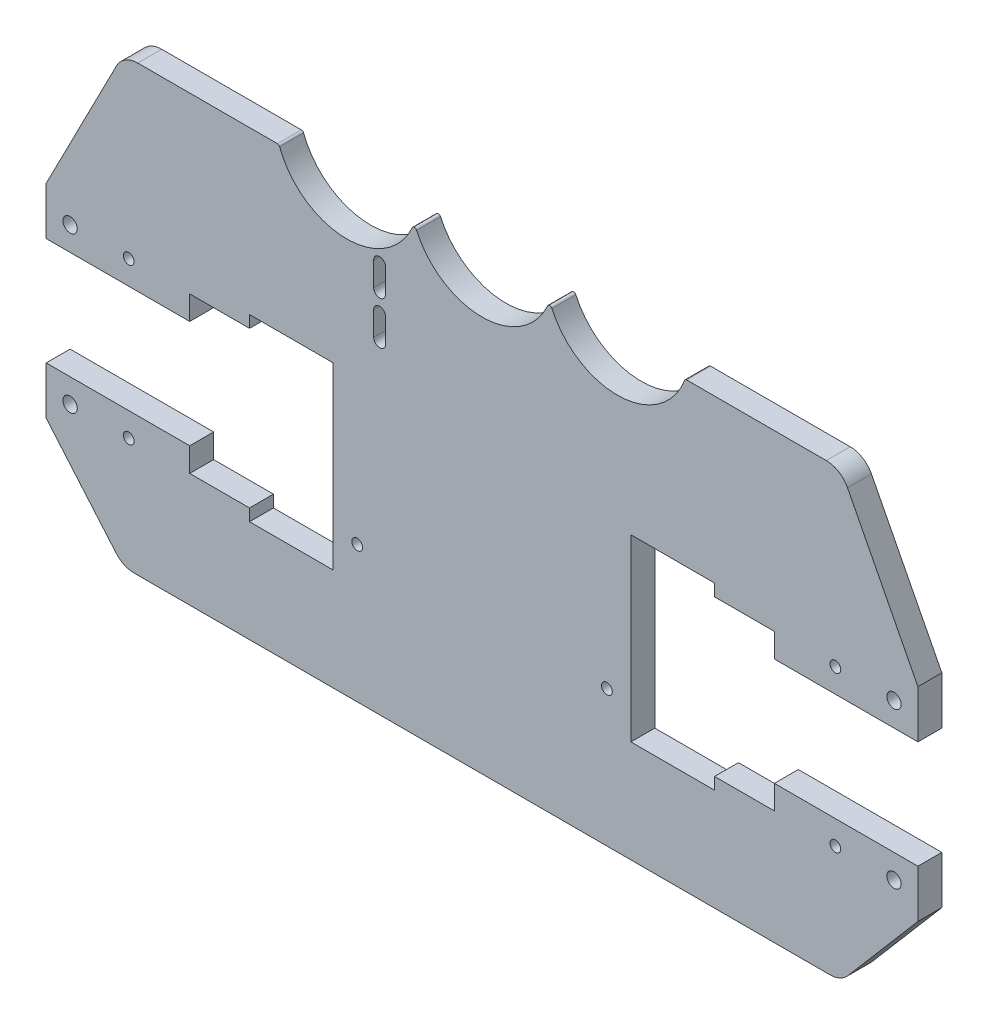
SolidWorks part; units mm, degrees
ref_plane "Plan de face" through (0, 0, 0) normal (0, 0, 1) x (1, 0, 0)
ref_plane "Plan de dessus" through (0, 0, 0) normal (0, 1, 0) x (1, 0, 0)
ref_plane "Plan de droite" through (0, 0, 0) normal (1, 0, 0) x (0, 0, -1)
sketch "Esquisse3" plane through (0, 0, 0) normal (0, 0, 1) x (1, 0, 0)
  line L0 (-182.2, 42.5) -> (-150, 105.2)
  line L1 (-182.2, 42.5) -> (182.2, 42.5)
  line L2 (-182.2, 42.5) -> (-182.2, -42.5)
  line L3 (-182.2, -42.5) -> (182.2, -42.5)
  line L4 (182.2, 42.5) -> (182.2, -42.5)
  line L5 (-150, 105.2) -> (150, 105.2)
  line L6 (-150, 105.2) -> (-150, 42.5)
  line L7 (-150, 42.5) -> (150, 42.5)
  line L8 (150, 105.2) -> (150, 42.5)
  line L9 (-150, -80.2) -> (150, -80.2)
  line L10 (-150, -80.2) -> (-150, -42.5)
  line L11 (-150, -42.5) -> (150, -42.5)
  line L12 (150, -80.2) -> (150, -42.5)
  line L13 (150, 105.2) -> (182.2, 42.5)
  line L14 (182.2, -42.5) -> (150, -80.2)
  line L15 (-150, -80.2) -> (-182.2, -42.5)
  dimension "D1" = 85
  dimension "D2" = 300
  dimension "D3" = 300
  dimension "D4" = 32.2
  dimension "D5" = 0
  dimension "D6" = 32.2
  dimension "D7" = 37.7
  dimension "D8" = 62.7
  dimension "D9" = 150
  dimension "D10" = 42.5
extrude "Boss.-Extru.1" add sketch "Esquisse3" along normal blind 10 contours L4 L1 L2 L3 | L8 L5 L6 L1 | L9 L12 L3 L10 | L6 L0 L1 | L15 L10 L3 | L14 L3 L12 | L13 L8 L1
sketch "Esquisse4" plane through (0, 0, 10) normal (0, 0, 1) x (1, 0, 0)
  line L1 (-182.2, 32.5) -> (-97.2, 32.5)
  line L2 (-182.2, 32.5) -> (-182.2, -32.5)
  line L3 (-182.2, -32.5) -> (-97.2, -32.5)
  line L4 (-97.2, 32.5) -> (-97.2, -32.5)
  line L5 (-97.2, -37.5) -> (-62.2, -37.5)
  line L6 (-97.2, -37.5) -> (-97.2, 37.5)
  line L7 (-97.2, 37.5) -> (-62.2, 37.5)
  line L8 (-62.2, -37.5) -> (-62.2, 37.5)
  line L9 (182.2, 32.5) -> (97.2, 32.5)
  line L10 (182.2, 32.5) -> (182.2, -32.5)
  line L11 (182.2, -32.5) -> (97.2, -32.5)
  line L12 (97.2, 32.5) -> (97.2, -32.5)
  line L13 (97.2, 37.5) -> (62.2, 37.5)
  line L14 (97.2, 37.5) -> (97.2, -37.5)
  line L15 (97.2, -37.5) -> (62.2, -37.5)
  line L16 (62.2, 37.5) -> (62.2, -37.5)
  line L17 (-182.2, 32.5) -> (-122.2, 32.5)
  line L18 (-182.2, 32.5) -> (-182.2, 22.5)
  line L19 (-182.2, 22.5) -> (-122.2, 22.5)
  line L20 (-122.2, 32.5) -> (-122.2, 22.5)
  line L21 (-182.2, -32.5) -> (-122.2, -32.5)
  line L22 (-182.2, -32.5) -> (-182.2, -22.5)
  line L23 (-182.2, -22.5) -> (-122.2, -22.5)
  line L24 (-122.2, -32.5) -> (-122.2, -22.5)
  line L25 (182.2, 32.5) -> (122.2, 32.5)
  line L26 (182.2, 32.5) -> (182.2, 22.5)
  line L27 (182.2, 22.5) -> (122.2, 22.5)
  line L28 (122.2, 32.5) -> (122.2, 22.5)
  line L29 (182.2, -32.5) -> (122.2, -32.5)
  line L30 (182.2, -32.5) -> (182.2, -22.5)
  line L31 (182.2, -22.5) -> (122.2, -22.5)
  line L32 (122.2, -32.5) -> (122.2, -22.5)
  line L34 (-182.2, 42.5) -> (-182.2, -42.5) construction
  line M16 (182.2, -42.5) -> (182.2, 42.5)
  line M20 (-182.2, 42.5) -> (-182.2, -42.5)
  dimension "D1" = 85
  dimension "D2" = 5
  dimension "D3" = 5
  dimension "D4" = 35
  dimension "D5" = 85
  dimension "D6" = 85
  dimension "D7" = 35
  dimension "D8" = 85
  dimension "D9" = 5
  dimension "D10" = 5
  dimension "D11" = 0
  dimension "D12" = 60
  dimension "D13" = 10
  dimension "D14" = 10
  dimension "D15" = 0
  dimension "D16" = 10
  dimension "D17" = 10
  dimension "D18" = 60
  dimension "D19" = 10
  dimension "D20" = 10
  dimension "D21" = 0
  dimension "D22" = 10
  dimension "D23" = 10
extrude "Enlèv. mat.-Extru.1" cut sketch "Esquisse4" against normal blind 10 contours L4 L1 L3 M20 | L5 L8 L7 L6 L4 | L13 L16 L15 L14 L12 | L9 L12 L11 M16
sketch "Esquisse5" plane through (0, 0, 10) normal (0, 0, 1) x (1, 0, 0)
  line L1 (-150, 105.2) -> (150, 105.2) construction
  arc A0 (28.2843, 105.2) -> (-28.2843, 105.2) centre (0, 115.2) cw
  arc A1 (-28.2843, 105.2) -> (-84.8528, 105.2) centre (-56.5685, 115.2) cw
  arc A2 (28.2843, 105.2) -> (84.8528, 105.2) centre (56.5685, 115.2) ccw
  point P4 (0, 80.2)
  point P6 (0, 80.2)
  point P11 (0, 80.2)
  point P12 (0, 80.2)
  point P13 (0, 0)
  point P14 (0, 0)
  point P15 (0, 80.2)
  dimension "D1" = 10
  dimension "D2" = 30
  dimension "D3" = 30
  dimension "D6" = 30
  dimension "D4" = 10
  dimension "D5" = 10
extrude "Enlèv. mat.-Extru.2" cut sketch "Esquisse5" against normal blind 10 and the other way through all
sketch "Esquisse11" plane through (0, 0, 10) normal (0, 0, 1) x (1, 0, 0)
  line L0 (182.2, 42.5) -> (182.2, 22.5) construction
  line L1 (-182.2, 42.5) -> (-162.2, 42.5)
  line L2 (-182.2, 42.5) -> (-182.2, 22.5)
  line L3 (-182.2, 22.5) -> (-162.2, 22.5)
  line L4 (-162.2, 42.5) -> (-162.2, 22.5)
  line L6 (182.2, -22.5) -> (182.2, -42.5) construction
  line L7 (-182.2, -22.5) -> (-162.2, -22.5)
  line L8 (-182.2, -22.5) -> (-182.2, -42.5)
  line L9 (-182.2, -42.5) -> (-162.2, -42.5)
  line L10 (-162.2, -22.5) -> (-162.2, -42.5)
  line L11 (182.2, 22.5) -> (122.2, 22.5) construction
  line L12 (162.2, 42.5) -> (182.2, 42.5)
  line L13 (162.2, 42.5) -> (162.2, 22.5)
  line L14 (162.2, 22.5) -> (182.2, 22.5)
  line L15 (182.2, 42.5) -> (182.2, 22.5)
  line L16 (162.2, -22.5) -> (182.2, -22.5)
  line L17 (162.2, -22.5) -> (162.2, -42.5)
  line L18 (162.2, -42.5) -> (182.2, -42.5)
  line L19 (182.2, -22.5) -> (182.2, -42.5)
  line L20 (-182.2, -22.5) -> (-182.2, -42.5) construction
  line L22 (-182.2, 42.5) -> (-182.2, 22.5) construction
  line L23 (182.2, -22.5) -> (122.2, -22.5) construction
  line L24 (-182.2, -22.5) -> (-122.2, -22.5) construction
  line L25 (-182.2, 22.5) -> (-122.2, 22.5) construction
  point P24 (172.2, 22.5)
  dimension "D1" = 20
  dimension "D2" = 20
  dimension "D3" = 0
  dimension "D4" = 0
  dimension "D5" = 20
  dimension "D6" = 20
  dimension "D7" = 0
  dimension "D8" = 0
  dimension "D9" = 20
  dimension "D10" = 20
  dimension "D11" = 20
  dimension "D12" = 20
  dimension "D13" = 0
  dimension "D14" = 0
  dimension "D15" = 0
  dimension "D16" = 0
sketch "Esquisse10" plane through (0, 0, 10) normal (0, 0, 1) x (1, 0, 0)
  line L1 (-182.2, 42.5) -> (-162.2, 42.5) construction
  line L2 (162.2, -22.5) -> (162.2, -42.5) construction
  line L3 (-182.2, 22.5) -> (-162.2, 22.5) construction
  line L4 (-162.2, 42.5) -> (-162.2, 22.5) construction
  line L5 (-182.2, -22.5) -> (-182.2, -42.5) construction
  line L6 (-182.2, -22.5) -> (-162.2, -22.5) construction
  line L8 (162.2, 42.5) -> (182.2, 42.5) construction
  line L10 (162.2, 42.5) -> (162.2, 22.5) construction
  line L11 (182.2, -22.5) -> (182.2, -42.5) construction
  line L12 (162.2, -22.5) -> (182.2, -22.5) construction
  line L13 (162.2, -42.5) -> (182.2, -42.5) construction
  line L15 (-162.2, -22.5) -> (-162.2, -42.5) construction
  circle A1 centre (-147.7, 32.5) radius 2.25
  circle A2 centre (-172.2, 32.5) radius 3
  circle A3 centre (-172.2, -32.5) radius 3
  circle A4 centre (-147.7, -32.5) radius 2.25
  circle A6 centre (172.2, 32.5) radius 3
  circle A8 centre (147.7, 32.5) radius 2.25
  circle A9 centre (172.2, -32.5) radius 3
  circle A10 centre (147.7, -32.5) radius 2.25
  dimension "D4" = 4.5
  dimension "D9" = 6
  dimension "D10" = 6
  dimension "D17" = 6
  dimension "D18" = 4.5
  dimension "D24" = 4.5
  dimension "D28" = 6
  dimension "D35" = 4.5
  dimension "D15" = 14.5
  dimension "D16" = 14.5
  dimension "D5" = 14.5
  dimension "D13" = 14.5
  dimension "D6" = 10
  dimension "D7" = 10
  dimension "D8" = 10
  dimension "D11" = 10
  dimension "D12" = 10
  dimension "D14" = 10
  dimension "D22" = 10
  dimension "D23" = 10
  dimension "D27" = 10
  dimension "D29" = 10
  dimension "D30" = 10
  dimension "D34" = 10
extrude "Enlèv. mat.-Extru.3" cut sketch "Esquisse10" against normal blind 10
sketch "Esquisse13" plane through (0, 0, 10) normal (0, 0, 1) x (1, 0, 0)
  line L0 (-62.2, -37.5) -> (-62.2, 37.5) construction
  line L1 (-62, 1.8) -> (62, 1.8)
  line L2 (-62, 1.8) -> (-62, -8.2)
  line L3 (-62, -8.2) -> (62, -8.2)
  line L4 (62, 1.8) -> (62, -8.2)
  line L5 (62.2, 37.5) -> (62.2, -37.5) construction
  line L7 (-150, -80.2) -> (150, -80.2) construction
  dimension "D1" = 0.2
  dimension "D2" = 0.2
  dimension "D3" = 10
  dimension "D4" = 72
sketch "Esquisse15" plane through (0, 0, 10) normal (0, 0, 1) x (1, 0, 0)
  line L1 (-62.2, -37.5) -> (-62.2, 37.5) construction
  line L2 (62.2, 37.5) -> (62.2, -37.5) construction
  line L4 (-62, -8.2) -> (62, -8.2) construction
  circle A0 centre (-52.2, -23.2) radius 2.25
  circle A1 centre (52.2, -23.2) radius 2.25
  dimension "D1" = 4.5
  dimension "D2" = 4.5
  dimension "D4" = 15
  dimension "D3" = 15
  dimension "D5" = 10
  dimension "D6" = 10
extrude "Enlèv. mat.-Extru.4" cut sketch "Esquisse15" against normal blind 10
fillet "Congé1" radius 10 4 edges at (150, 105.2, 5) (150, -80.2, 5) (-150, 105.2, 5) (-150, -80.2, 5)
fillet "Congé3" radius 1 4 edges at (-84.8528, 105.2, 5) (-28.2843, 105.2, 5) (28.2843, 105.2, 5) (84.8528, 105.2, 5)
sketch "Esquisse16" plane through (0, 0, 10) normal (0, 0, 1) x (1, 0, 0)
  line L0 (-182.2, 42.5) -> (-182.2, 22.5) construction
  line L1 (-17.81, 59.2) -> (-27.81, 59.2)
  line L2 (-17.81, 59.2) -> (-17.81, 89.2)
  line L3 (-17.81, 89.2) -> (-27.81, 89.2)
  line L4 (-27.81, 59.2) -> (-27.81, 89.2)
  line L5 (-143.8939, 105.2) -> (-85.5513, 105.2) construction
  dimension "D1" = 154.39
  dimension "D2" = 16
  dimension "D3" = 30
  dimension "D4" = 10
sketch "Esquisse17" plane through (0, 0, 10) normal (0, 0, 1) x (1, 0, 0)
  line L0 (-42.81, 83.2) -> (-42.81, 73.2) construction
  line L1 (-40.31, 83.2) -> (-40.31, 73.2)
  line L2 (-45.31, 83.2) -> (-45.31, 73.2)
  line L3 (-42.81, 65.2) -> (-42.81, 55.2) construction
  line L4 (-40.31, 65.2) -> (-40.31, 55.2)
  line L5 (-45.31, 65.2) -> (-45.31, 55.2)
  line L6 (-27.81, 59.2) -> (-27.81, 89.2) construction
  line L7 (-17.81, 89.2) -> (-27.81, 89.2) construction
  line L8 (-17.81, 59.2) -> (-27.81, 59.2) construction
  arc A0 (-40.31, 83.2) -> (-45.31, 83.2) centre (-42.81, 83.2) ccw
  arc A1 (-45.31, 73.2) -> (-40.31, 73.2) centre (-42.81, 73.2) ccw
  arc A2 (-40.31, 65.2) -> (-45.31, 65.2) centre (-42.81, 65.2) ccw
  arc A3 (-45.31, 55.2) -> (-40.31, 55.2) centre (-42.81, 55.2) ccw
  point P2 (-42.81, 78.2)
  point P7 (-42.81, 60.2)
  dimension "D6" = 2.5
  dimension "D7" = 2.5
  dimension "D1" = 15
  dimension "D2" = 6
  dimension "D3" = 6
  dimension "D4" = 10
  dimension "D5" = 10
extrude "Enlèv. mat.-Extru.5" cut sketch "Esquisse17" against normal blind 10
